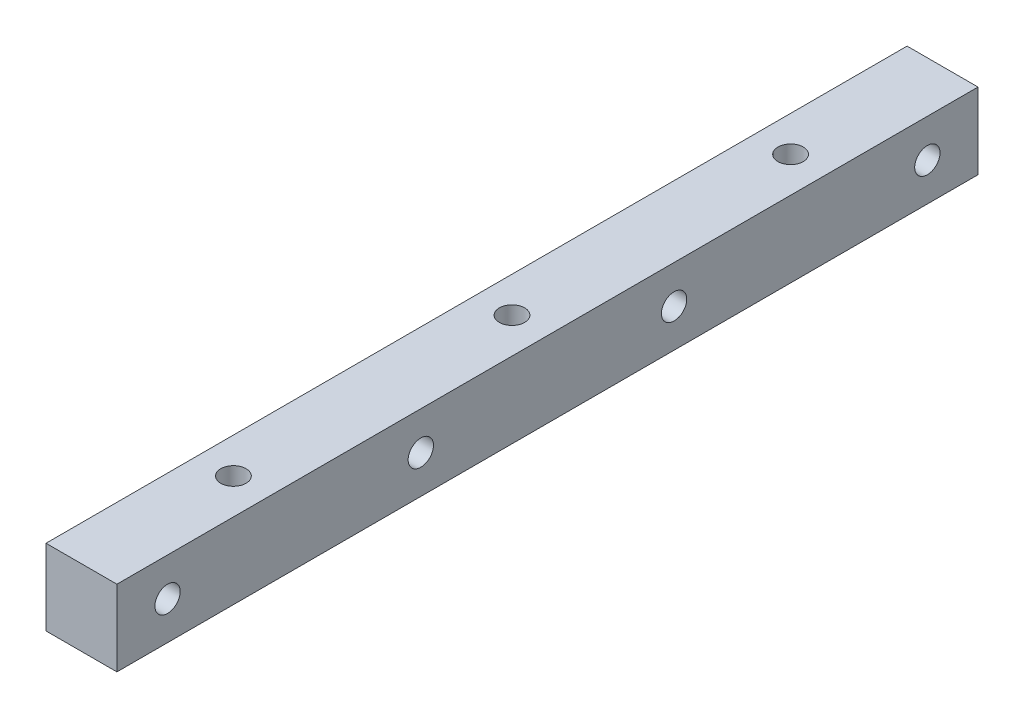
SolidWorks part; units mm, degrees
ref_plane "前视基准面" through (0, 0, 0) normal (0, 0, 1) x (1, 0, 0)
ref_plane "上视基准面" through (0, 0, 0) normal (0, 1, 0) x (1, 0, 0)
ref_plane "右视基准面" through (0, 0, 0) normal (1, 0, 0) x (0, 0, -1)
sketch "草图1" plane through (0, 0, 0) normal (0, 0, 1) x (1, 0, 0)
  line L0 (-2.8, 0) -> (-2.8, 6)
  line L1 (-2.8, 6) -> (2.8, 6)
  line L4 (2.8, 6) -> (2.8, 0)
  line L5 (2.8, 0) -> (-2.8, 0)
  point P6 (0, 0)
  dimension "D1" = 5.6
  dimension "D3" = 6
extrude "凸台-拉伸1" add sketch "草图1" along normal mid plane 68
sketch "草图4" plane through (0, 0, 0) normal (0, -1, 0) x (1, 0, 0)
  line L0 (2.8, 34) -> (2.8, -34) construction
  circle A0 centre (0, 0) radius 1
  circle A1 centre (0, 22) radius 1
  circle A2 centre (0, -22) radius 1
  dimension "D1" = 2
  dimension "D2" = 22
  dimension "D3" = 22
  dimension "D4" = 2.8
extrude "切除-拉伸3" cut sketch "草图4" against normal up to next
sketch "草图5" plane through (2.8, 0, 0) normal (1, 0, 0) x (0, 0, -1)
  line L0 (-34, 3) -> (34, 3) construction
  line L1 (-34, 0) -> (-34, 6) construction
  line L2 (34, 0) -> (34, 6) construction
  line L3 (0, 0) -> (0, 6) construction
  line L4 (-34, 6) -> (34, 6) construction
  circle A0 centre (-30, 3) radius 1
  circle A1 centre (-10, 3) radius 1
  circle A2 centre (10, 3) radius 1
  circle A3 centre (30, 3) radius 1
  dimension "D1" = 10
  dimension "D2" = 2
  dimension "D3" = 20
extrude "切除-拉伸4" cut sketch "草图5" against normal up to next
